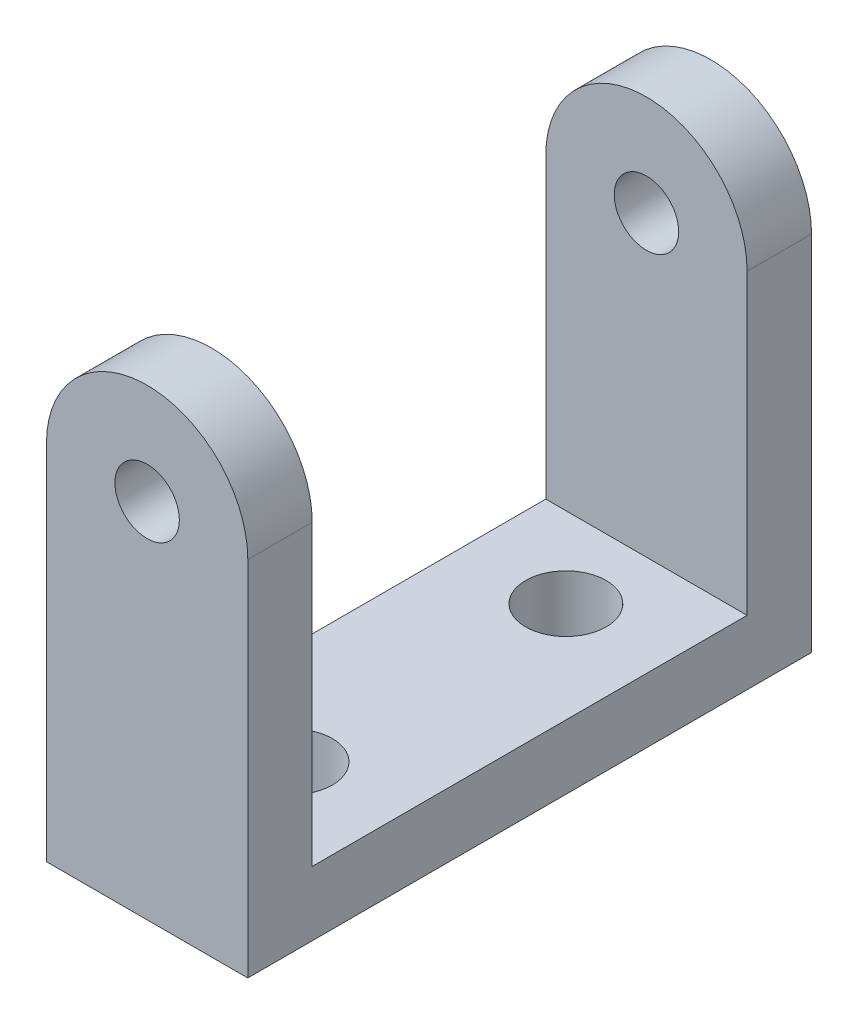
SolidWorks part; units mm, degrees
ref_plane "Piano frontale" through (0, 0, 0) normal (0, 0, 1) x (1, 0, 0)
ref_plane "Piano superiore" through (0, 0, 0) normal (0, 1, 0) x (1, 0, 0)
ref_plane "Piano destro" through (0, 0, 0) normal (1, 0, 0) x (0, 0, -1)
sketch "Schizzo1" plane through (0, 0, 0) normal (0, 0, 1) x (1, 0, 0)
  line L0 (-12.5, 0) -> (12.5, 0)
  line L1 (-12.5, 0) -> (-12.5, 45)
  line L2 (12.5, 0) -> (12.5, 45)
  circle A0 centre (0, 45) radius 4
  arc A1 (12.5, 45) -> (-12.5, 45) centre (0, 45) ccw
  point P3 (0, 0)
  dimension "D3" = 8
  dimension "D1" = 25
  dimension "D2" = 45
extrude "Estrusione-Estrusione1" add sketch "Schizzo1" along normal blind 70
sketch "Schizzo2" plane through (0, 0, 0) normal (1, 0, 0) x (0, 0, -1)
  line L0 (0, 57.5) -> (-70, 57.5) construction
  line L1 (-62, 57.5) -> (-8, 57.5)
  line L2 (-62, 57.5) -> (-62, 8)
  line L3 (-62, 8) -> (-8, 8)
  line L4 (-8, 57.5) -> (-8, 8)
  line L6 (-70, 0) -> (0, 0) construction
  point P7 (-35, 57.5)
  dimension "D1" = 8
  dimension "D2" = 8
extrude "Taglio-Estrusione1" cut sketch "Schizzo2" against normal through all both and the other way through all
sketch "Schizzo4" plane through (0, 0, 0) normal (0, -1, 0) x (1, 0, 0)
  line L0 (0, 18) -> (0, 52) construction
  line L2 (-12.5, 70) -> (12.5, 70) construction
  line L5 (-12.5, 70) -> (-12.5, 0) construction
  circle A0 centre (0, 18) radius 5
  circle A1 centre (0, 52) radius 5
  point P10 (0, 70)
  point P11 (-12.5, 35)
  point P12 (0, 35)
  dimension "D1" = 10
  dimension "D2" = 34
extrude "Taglio-Estrusione2" cut sketch "Schizzo4" against normal through all
